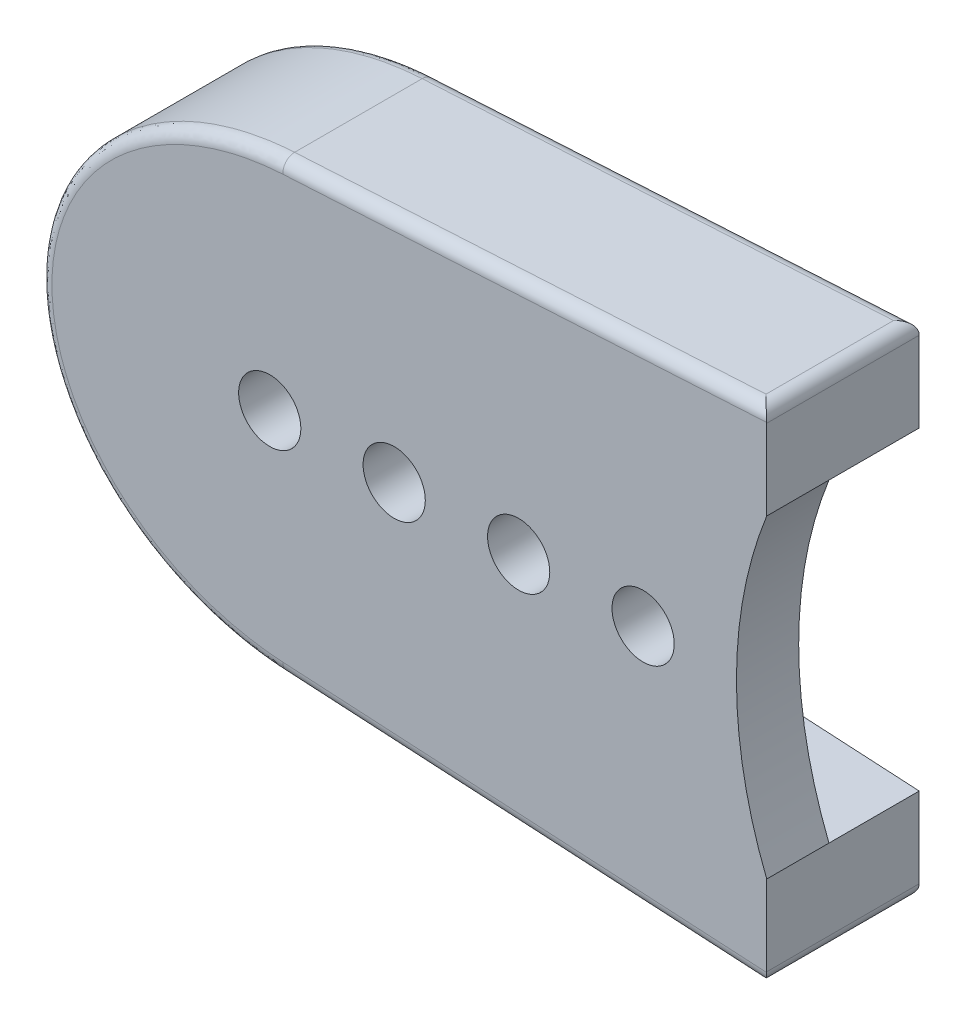
SolidWorks part; units mm, degrees
ref_plane "前视基准面" through (0, 0, 0) normal (0, 0, 1) x (1, 0, 0)
ref_plane "上视基准面" through (0, 0, 0) normal (0, 1, 0) x (1, 0, 0)
ref_plane "右视基准面" through (0, 0, 0) normal (1, 0, 0) x (0, 0, -1)
other "Configuration Table"
sketch "草图1" plane through (0, 0, 0) normal (0, 0, 1) x (1, 0, 0)
  line L10 (-14.0168, -2.0967) -> (-2.2919, -2.7498)
  line L11 (-2.2919, 2.7498) -> (-14.0168, 2.0967)
  line L12 (-14.0168, -2.0967) -> (-6.3135, -2.5258)
  line L13 (-6.3135, 2.5258) -> (-14.0168, 2.0967)
  circle A0 centre (-14.3, 0) radius 0.5 construction
  circle A1 centre (-10.3, 0) radius 0.5 construction
  circle A6 centre (-10.3, 0) radius 0.5
  circle A7 centre (-14.3, 0) radius 0.5
  circle A8 centre (-8.3, 0) radius 0.5 construction
  arc A9 (-14.0168, 2.0967) -> (-14.0168, -2.0967) centre (-13.9, 0) ccw
  arc A10 (-14.0168, 2.0967) -> (-14.0168, -2.0967) centre (-13.9, 0) ccw
  circle A11 centre (-8.3, 0) radius 0.5
  circle A12 centre (-12.3, 0) radius 0.5 construction
  circle A13 centre (-12.3, 0) radius 0.5
  arc A15 (-6.3135, 2.5258) -> (-6.3135, -2.5258) centre (0, 0) ccw
  arc A16 (-2.2864, 2.65) -> (-2.2864, -2.65) centre (0, 0) ccw construction
  circle A17 centre (-6.3, 0) radius 0.5 construction
  dimension "D1" = 0.1
extrude "凸台-拉伸1" add sketch "草图1" along normal blind 1
sketch "草图3" plane through (0, 0, 1) normal (0, 0, 1) x (1, 0, 0)
  line L0 (-6.3135, 4.0282) -> (-14.1002, 3.5944)
  line L1 (-14.1002, -3.5944) -> (-6.3135, -4.0282)
  line L2 (-6.3969, 4.0235) -> (-14.1002, 3.5944) construction
  line L3 (-6.3135, 2.5258) -> (-14.0168, 2.0967)
  line L4 (-14.0168, -2.0967) -> (-6.3135, -2.5258)
  line L6 (-6.3135, 2.5258) -> (-14.0168, 2.0967)
  line L7 (-14.0168, -2.0967) -> (-6.3135, -2.5258)
  line L9 (-14.1002, -3.5944) -> (-6.3969, -4.0235) construction
  line L10 (-6.3135, 2.5258) -> (-6.3135, 4.0282)
  line L11 (-6.3135, -2.5258) -> (-6.3135, -4.0282)
  arc A0 (-14.1002, 3.5944) -> (-14.1002, -3.5944) centre (-13.9, 0) ccw
  arc A1 (-14.0168, 2.0967) -> (-14.0168, -2.0967) centre (-13.9, 0) ccw
  arc A2 (-14.0168, 2.0967) -> (-14.0168, -2.0967) centre (-13.9, 0) ccw
  arc A5 (-6.3135, 2.5258) -> (-6.3135, -2.5258) centre (0, 0) ccw
  arc A6 (-6.3135, 2.5258) -> (-6.3135, -2.5258) centre (0, 0) ccw
  line M5 (-6.3135, 2.5258) -> (-14.0168, 2.0967)
  arc M6 (-14.0168, 2.0967) -> (-14.0168, -2.0967) centre (-13.9, 0) ccw
  line M7 (-14.0168, -2.0967) -> (-6.3135, -2.5258)
  dimension "D1" = 0
  dimension "D2" = 1.5
extrude "凸台-拉伸2" add sketch "草图3" against normal up to surface (2.45 mm away) contours L0 A0 L1 L11 L10 M7 M6 M5
sketch "草图4" plane through (0, 0, 1) normal (0, 0, 1) x (1, 0, 0)
  line L0 (-14.1002, -3.5944) -> (-6.3135, -4.0282) construction
  line L1 (-6.3135, 4.0282) -> (-14.1002, 3.5944) construction
  line L2 (-18, 3.4961) -> (-18, -2.582) construction
  line L3 (-17.5, 5.8123) -> (-17.5, -4.4146) construction
  arc A1 (-14.1002, 3.5944) -> (-14.1002, -3.5944) centre (-13.9, 0) ccw construction
  arc A2 (-14.1002, 3.5944) -> (-14.1002, -3.5944) centre (-13.9, 0) ccw
  ellipse E0 centre (-13.8321, 0) end of major axis (-9.6643, 0) minor radius 3.6019 (-14.1002, 3.5944) -> (-14.1002, -3.5944) ccw
  point P19 (-17.5267, -4.4146)
  dimension "D1" = 0.5
extrude "凸台-+" add sketch "草图4" against normal up to surface (2.45 mm away) up to face at (-10.8589, 0, -1.45)
fillet "圆角1" radius 0.2 8 edges at (-10.2069, -3.8113, -1.45) (-10.2069, -3.8113, 1) (-6.3135, -4.0282, -0.225) (-10.2069, 3.8113, -1.45) (-10.2069, 3.8113, 1) (-6.3135, 4.0282, -0.225) (-18, 0, 1) (-18, 0, -1.45)
